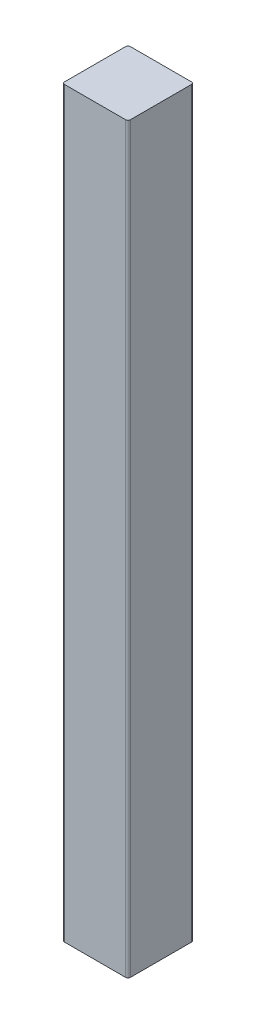
SolidWorks part; units mm, degrees
material "Pine"
ref_plane "Front Plane" through (0, 0, 0) normal (0, 0, 1) x (1, 0, 0)
ref_plane "Top Plane" through (0, 0, 0) normal (0, 1, 0) x (1, 0, 0)
ref_plane "Right Plane" through (0, 0, 0) normal (1, 0, 0) x (0, 0, -1)
sketch "Sketch1" plane through (0, 0, 0) normal (0, 1, 0) x (1, 0, 0)
  line L1 (-44.45, -44.45) -> (44.45, -44.45)
  line L2 (-44.45, -44.45) -> (-44.45, 44.45)
  line L3 (-44.45, 44.45) -> (44.45, 44.45)
  line L4 (44.45, -44.45) -> (44.45, 44.45)
  line L5 (-44.45, -44.45) -> (44.45, 44.45) construction
  line L6 (-44.45, 44.45) -> (44.45, -44.45) construction
  point P0 (0, 0)
  dimension "D1" = 88.9
  dimension "D2" = 88.9
extrude "Boss-Extrude1" add sketch "Sketch1" along normal blind 1004.8875
fillet "Fillet1" radius 3.175 4 edges at (-44.45, 502.4437, 44.45) (-44.45, 502.4437, -44.45) (44.45, 502.4437, -44.45) (44.45, 502.4437, 44.45)
